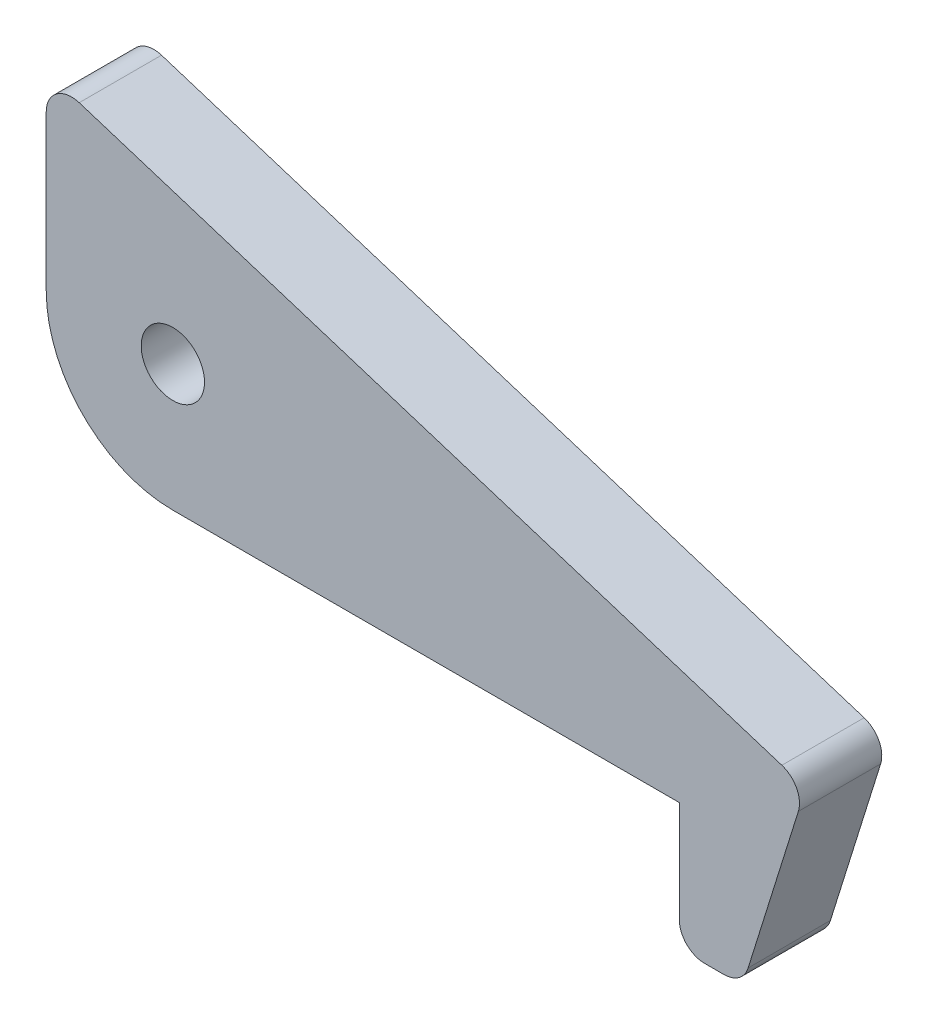
SolidWorks part; units mm, degrees
ref_plane "Front Plane" through (0, 0, 0) normal (0, 0, 1) x (1, 0, 0)
ref_plane "Top Plane" through (0, 0, 0) normal (0, 1, 0) x (1, 0, 0)
ref_plane "Right Plane" through (0, 0, 0) normal (1, 0, 0) x (0, 0, -1)
sketch "Sketch1" plane through (0, 0, 0) normal (0, 0, 1) x (1, 0, 0)
  line L1 (0, 0) -> (60, 0)
  line L2 (0, 0) -> (0, 35)
  line L3 (0, 35) -> (60, 35)
  line L4 (60, 0) -> (60, 35)
  dimension "D1" = 60
  dimension "D2" = 35
extrude "Boss-Extrude1" add sketch "Sketch1" along normal blind 6.5
sketch "Sketch2" plane through (0, 0, 6.5) normal (0, 0, 1) x (1, 0, 0)
  line L0 (60, 0) -> (60, 35) construction
  line L1 (0, 0) -> (50, 0)
  line L2 (0, 0) -> (0, 10)
  line L3 (0, 10) -> (50, 10)
  line L4 (50, 0) -> (50, 10)
  dimension "D1" = 10
  dimension "D2" = 10
extrude "Cut-Extrude1" cut sketch "Sketch2" against normal through all
fillet "Fillet1" radius 10 1 edges at (0, 10, 3.25)
sketch "Sketch3" plane through (0, 0, 6.5) normal (0, 0, 1) x (1, 0, 0)
  line L0 (50, 10) -> (10, 10) construction
  line L1 (0, 35) -> (0, 20) construction
  circle A0 centre (10, 20) radius 2.5
  dimension "D1" = 5
  dimension "D2" = 10
  dimension "D3" = 10
extrude "Cut-Extrude2" cut sketch "Sketch3" against normal up to next
sketch "Sketch4" plane through (0, 0, 6.5) normal (0, 0, 1) x (1, 0, 0)
  line L0 (55, 0) -> (60, 16)
  line L1 (50, 0) -> (60, 0) construction
  line L3 (60, 0) -> (60, 35) construction
  line L4 (60, 0) -> (55, 0)
  line L5 (60, 16) -> (60, 0)
  dimension "D1" = 16
extrude "Cut-Extrude3" cut sketch "Sketch4" against normal through all
sketch "Sketch5" plane through (0, 0, 6.5) normal (0, 0, 1) x (1, 0, 0)
  line L0 (0, 35) -> (60, 16)
  line L1 (60, 16) -> (60, 35)
  line L2 (60, 35) -> (0, 35)
extrude "Cut-Extrude4" cut sketch "Sketch5" against normal through all
fillet "Fillet6" radius 2 1 edges at (50, 0, 3.25)
fillet "Fillet7" radius 2 1 edges at (55, 0, 3.25)
fillet "Fillet8" radius 2 1 edges at (60, 16, 3.25)
fillet "Fillet9" radius 2 1 edges at (0, 35, 3.25)
